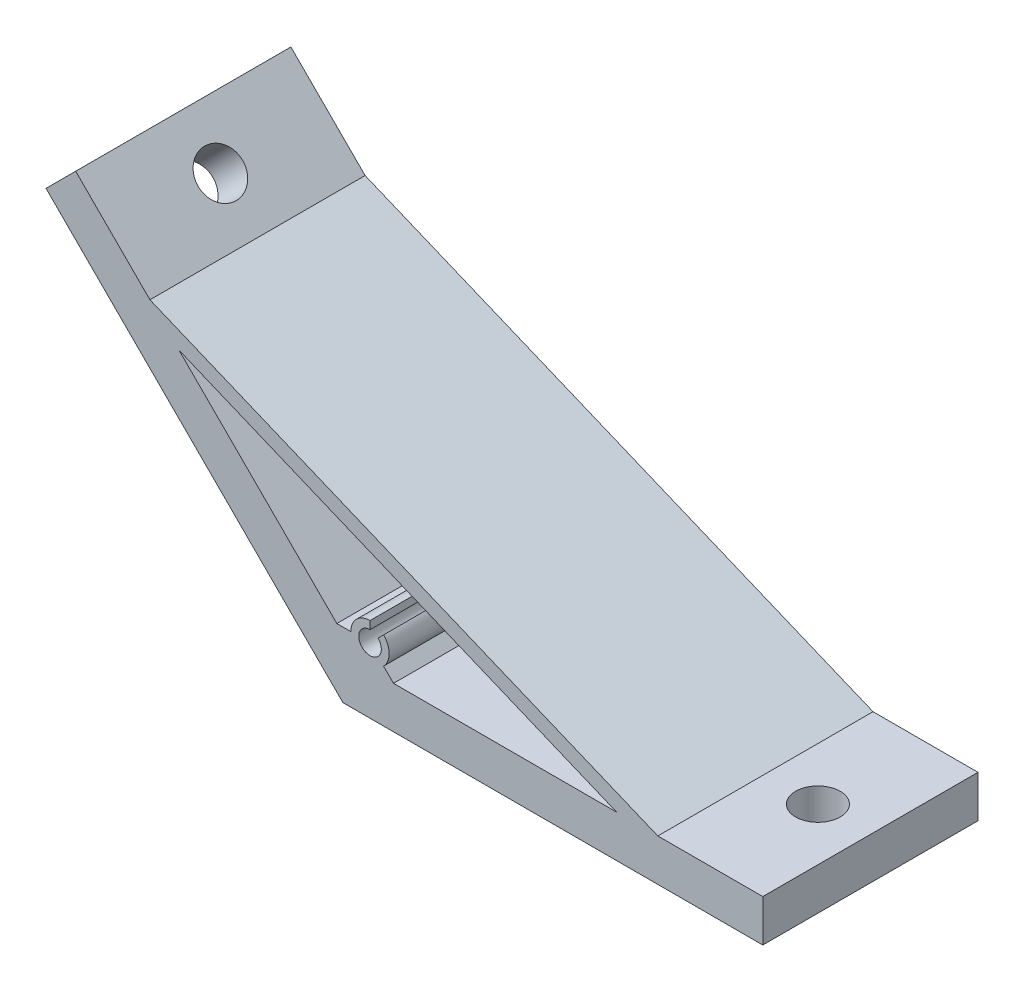
SolidWorks part; units mm, degrees
ref_plane "前视基准面" through (0, 0, 0) normal (0, 0, 1) x (1, 0, 0)
ref_plane "上视基准面" through (0, 0, 0) normal (0, 1, 0) x (1, 0, 0)
ref_plane "右视基准面" through (0, 0, 0) normal (1, 0, 0) x (0, 0, -1)
sketch "草图1" plane through (0, 0, 0) normal (0, 0, 1) x (1, 0, 0)
  line B0 (80, 0) -> (0, 0)
  line B1 (80, 8) -> (60, 8)
  line B2 (52.1606, 8) -> (9.6386, 8)
  line B3 (0, 0) -> (-56.5685, 56.5685)
  line B4 (-1.1587, 12.4724) -> (-31.2263, 42.54)
  line B5 (-36.7696, 48.0833) -> (-50.9117, 62.2254)
  line B6 (-50.9117, 62.2254) -> (-56.5685, 56.5685)
  line B7 (80, 8) -> (80, 0)
  line B8 (-1.1587, 12.4724) -> (1.5162, 12.4724)
  line B9 (9.6386, 8) -> (7.7472, 9.8914)
  line B10 (6.6865, 13.9927) -> (7.7472, 15.0533)
  line B11 (5.1662, 14.6224) -> (5.1662, 16.1224)
  line B12 (-36.7696, 48.0833) -> (60, 8)
  line B13 (-31.2263, 42.54) -> (52.1606, 8)
  arc B14 (5.1662, 14.6224) -> (6.6865, 13.9927) centre (5.1662, 12.4724) ccw
  arc B15 (7.7472, 9.8914) -> (7.7472, 15.0533) centre (5.1662, 12.4724) ccw
  arc B16 (5.1662, 16.1224) -> (1.5162, 12.4724) centre (5.1662, 12.4724) ccw
sketch_block_instance "A$C053212F5-1"
sketch_block "A$C053212F5"
extrude "凸台-拉伸1" add sketch "草图1" along normal mid plane 41
sketch "草图3" plane through (0, 8, 0) normal (0, 1, 0) x (1, 0, 0)
  line L0 (80, -20.5) -> (80, 20.5) construction
  circle A0 centre (70, 0) radius 4.25
  dimension "D1" = 10
extrude "切除-拉伸1" cut sketch "草图3" against normal through all
sketch "草图4" plane through (11.6152, 28.0416, 0) normal (0.3827, 0.9239, 0) x (0.9239, -0.3827, 0)
  line L0 (0, -20.5) -> (0, 20.5) construction
  line L1 (52.3713, -20.5) -> (-52.3713, -20.5) construction
  line L2 (52.3713, 20.5) -> (-52.3713, 20.5) construction
ref_plane "基准面2" through (0, 0, 0) normal (-0.9239, 0.3827, 0) x (0, 0, 1)
mirror "镜向1" about plane through (0, 0, 0) normal (-0.9239, 0.3827, 0) of "切除-拉伸1"
